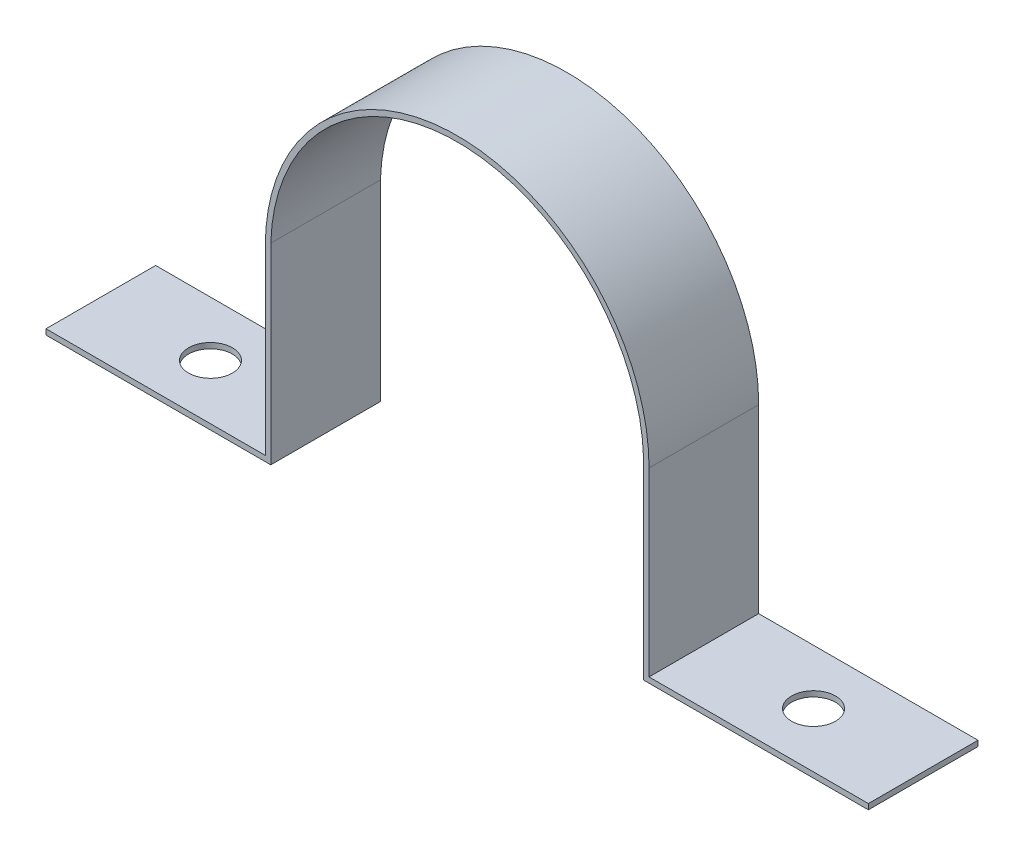
SolidWorks part; units mm, degrees
ref_plane "Alzado" through (0, 0, 0) normal (0, 0, 1) x (1, 0, 0)
ref_plane "Planta" through (0, 0, 0) normal (0, 1, 0) x (1, 0, 0)
ref_plane "Vista lateral" through (0, 0, 0) normal (1, 0, 0) x (0, 0, -1)
sketch "Croquis1" plane through (0, 0, 0) normal (0, 0, 1) x (1, 0, 0)
  line L7 (0, 0) -> (0, -10.2182) construction
  line L12 (-17.5, 0) -> (-17.5, -16.5074)
  line L14 (17, 0.5) -> (17, -17.0074)
  line L16 (-17, 0.5) -> (-17, -17.0074)
  line L17 (17, 17.0074) -> (-17, -17.0074) construction
  line L18 (17, -17.0074) -> (-17, 17.0074) construction
  line L20 (17.5, 0) -> (17.5, -16.5074)
  line L22 (-17, -17.0074) -> (-37.5, -17.0074)
  line L23 (-37.5, -17.0074) -> (-37.5, -16.5074)
  line L24 (-37.5, -16.5074) -> (-17.5, -16.5074)
  line L25 (-17.5, 17.5074) -> (-17.5, -17.5074) construction
  line L26 (17.5, -17.5074) -> (-17.5, -17.5074) construction
  line L27 (37.5, -16.5074) -> (17.5, -16.5074)
  line L28 (37.5, -17.0074) -> (37.5, -16.5074)
  line L29 (17, -17.0074) -> (37.5, -17.0074)
  line L30 (17.5, 17.5074) -> (17.5, -17.5074) construction
  line L31 (17, -17.0074) -> (-17, -17.0074) construction
  line L32 (17.5, 17.5074) -> (-17.5, 17.5074) construction
  line L33 (17, 17.0074) -> (-17, 17.0074) construction
  line L34 (-17, 17.0074) -> (-17, -17.0074) construction
  line L35 (17, 17.0074) -> (17, -17.0074) construction
  arc A1 (17.5, 0) -> (-17.5, 0) centre (0, 0) ccw
  arc A4 (17, 0.5) -> (-17, 0.5) centre (0, 0) ccw
  dimension "D1" = 17.5
  dimension "D2" = 0.5
  dimension "D6" = 17.0074
  dimension "D3" = 20
  dimension "D5" = 17.5074
extrude "Saliente-Extruir1" add sketch "Croquis1" along normal blind 10
sketch "Croquis2" plane through (0, -16.5074, 0) normal (0, 1, 0) x (1, 0, 0)
  line L0 (-17.5, -10) -> (-17.5, 0) construction
  line L1 (17.5, -10) -> (17.5, 0) construction
  line L2 (-37.5, -10) -> (-37.5, 0) construction
  circle A0 centre (-27.5, -5) radius 2
  circle A1 centre (27.5, -5) radius 2
  point P10 (-37.5, -5)
  dimension "D1" = 10
  dimension "D3" = 4
  dimension "D2" = 10
extrude "Cortar-Extruir1" cut sketch "Croquis2" against normal blind 10
